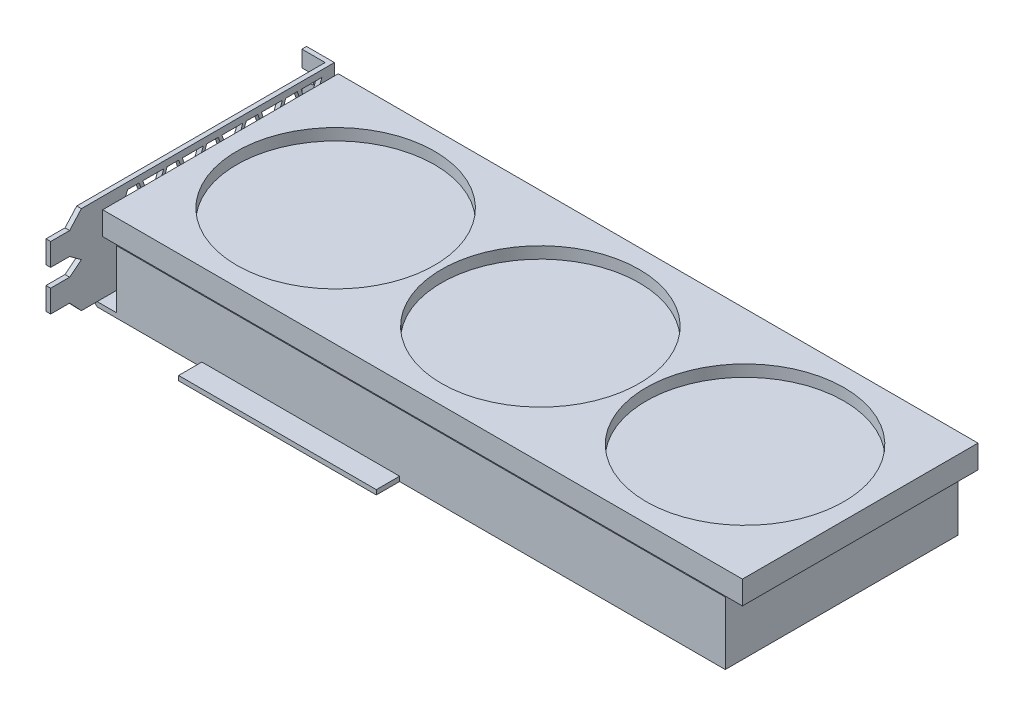
SolidWorks part; units mm, degrees
ref_plane "Front" through (0, 0, 0) normal (0, 0, 1) x (1, 0, 0)
ref_plane "Top" through (0, 0, 0) normal (0, 1, 0) x (1, 0, 0)
ref_plane "Right" through (0, 0, 0) normal (1, 0, 0) x (0, 0, -1)
sketch "Sketch5" plane through (0, 0, 0) normal (0, 1, 0) x (1, 0, 0)
  line L0 (-103.8802, -0.3761) -> (-58.8802, -0.3761)
  line L1 (-103.8802, 99.6239) -> (166.1198, 99.6239)
  line L2 (-103.8802, 99.6239) -> (-103.8802, -0.3761)
  line L4 (166.1198, 99.6239) -> (166.1198, -0.3761)
  line L6 (-58.8802, -0.3761) -> (-58.8802, -10.3761)
  line L7 (-58.8802, -10.3761) -> (26.1198, -10.3761)
  line L8 (26.1198, -0.3761) -> (26.1198, -10.3761)
  line L9 (26.1198, -0.3761) -> (166.1198, -0.3761)
  dimension "D1" = 100
  dimension "D2" = 270
  dimension "D3" = 10
  dimension "D4" = 85
  dimension "D5" = 45
extrude "Boss-Extrude3" add sketch "Sketch5" along normal blind 2 contours L2 L0 L6 L7 L8 L9 L4 L1
sketch "Sketch6" plane through (-103.8802, 0, 0) normal (-1, 0, 0) x (0, 0, 1)
  line L0 (20.3761, 24.7157) -> (20.3761, 34.3764)
  line L1 (-99.6239, 2) -> (20.3761, 2) construction
  line L2 (-99.6239, 2) -> (-99.6239, 40)
  line L3 (-99.6239, 40) -> (20.3761, 40) construction
  line L4 (20.3761, 2) -> (20.3761, 40) construction
  line L5 (20.3761, 34.3764) -> (12.2118, 34.3764)
  line L6 (12.2118, 34.3764) -> (7.1586, 40)
  line L7 (7.1586, 40) -> (-99.6239, 40)
  line L8 (20.3761, 24.7157) -> (12.2118, 24.7157)
  line L9 (12.2118, 24.7157) -> (7.1586, 21)
  line L10 (7.1586, 21) -> (12.2118, 17.008)
  line L11 (12.2118, 17.008) -> (20.3761, 17.008)
  line L12 (20.3761, 17.008) -> (20.3761, 7.3474)
  line L13 (20.3761, 7.3474) -> (12.2118, 7.3474)
  line L14 (12.2118, 7.3474) -> (7.1586, 2)
  line L15 (7.1586, 2) -> (-99.6239, 2)
  line L16 (-96.2244, 37.1678) -> (-87.2244, 37.1678)
  line L17 (-87.2244, 37.1678) -> (-89.2435, 31.6296)
  line L18 (-89.2435, 31.6296) -> (-94.2053, 31.6296)
  line L19 (-94.2053, 31.6296) -> (-96.2244, 37.1678)
  line L20 (-94.2053, 30.1428) -> (-89.2435, 30.1428)
  line L21 (-89.2435, 30.1428) -> (-87.2244, 24.6046)
  line L22 (-87.2244, 24.6046) -> (-96.2244, 24.6046)
  line L23 (-96.2244, 24.6046) -> (-94.2053, 30.1428)
  line L24 (-87.6768, 31.6186) -> (-85.6577, 37.1568)
  line L25 (-85.6577, 37.1568) -> (-80.6959, 37.1568)
  line L26 (-80.6959, 37.1568) -> (-78.6768, 31.6186)
  line L27 (-78.6768, 31.6186) -> (-87.6768, 31.6186)
  line L28 (-87.7069, 30.1428) -> (-78.7069, 30.1428)
  line L29 (-78.7069, 30.1428) -> (-80.726, 24.6046)
  line L30 (-80.726, 24.6046) -> (-85.6878, 24.6046)
  line L31 (-85.6878, 24.6046) -> (-87.7069, 30.1428)
  line L33 (-77.2053, 31.6296) -> (-79.2244, 37.1678)
  line L34 (-79.2244, 37.1678) -> (-70.2244, 37.1678)
  line L35 (-70.2244, 37.1678) -> (-72.2435, 31.6296)
  line L36 (-72.2435, 31.6296) -> (-77.2053, 31.6296)
  line L37 (-61.6768, 31.6186) -> (-70.6768, 31.6186)
  line L38 (-70.6768, 31.6186) -> (-68.6577, 37.1568)
  line L39 (-68.6577, 37.1568) -> (-63.6959, 37.1568)
  line L40 (-63.6959, 37.1568) -> (-61.6768, 31.6186)
  line L41 (-68.6878, 24.6046) -> (-70.7069, 30.1428)
  line L42 (-70.7069, 30.1428) -> (-61.7069, 30.1428)
  line L43 (-61.7069, 30.1428) -> (-63.726, 24.6046)
  line L44 (-63.726, 24.6046) -> (-68.6878, 24.6046)
  line L45 (-79.2244, 24.6046) -> (-77.2053, 30.1428)
  line L46 (-77.2053, 30.1428) -> (-72.2435, 30.1428)
  line L47 (-72.2435, 30.1428) -> (-70.2244, 24.6046)
  line L48 (-70.2244, 24.6046) -> (-79.2244, 24.6046)
  line L50 (-60.2053, 31.6296) -> (-62.2244, 37.1678)
  line L51 (-62.2244, 37.1678) -> (-53.2244, 37.1678)
  line L52 (-53.2244, 37.1678) -> (-55.2435, 31.6296)
  line L53 (-55.2435, 31.6296) -> (-60.2053, 31.6296)
  line L54 (-44.6768, 31.6186) -> (-53.6768, 31.6186)
  line L55 (-53.6768, 31.6186) -> (-51.6577, 37.1568)
  line L56 (-51.6577, 37.1568) -> (-46.6959, 37.1568)
  line L57 (-46.6959, 37.1568) -> (-44.6768, 31.6186)
  line L58 (-51.6878, 24.6046) -> (-53.7069, 30.1428)
  line L59 (-53.7069, 30.1428) -> (-44.7069, 30.1428)
  line L60 (-44.7069, 30.1428) -> (-46.726, 24.6046)
  line L61 (-46.726, 24.6046) -> (-51.6878, 24.6046)
  line L62 (-62.2244, 24.6046) -> (-60.2053, 30.1428)
  line L63 (-60.2053, 30.1428) -> (-55.2435, 30.1428)
  line L64 (-55.2435, 30.1428) -> (-53.2244, 24.6046)
  line L65 (-53.2244, 24.6046) -> (-62.2244, 24.6046)
  line L67 (-43.2053, 31.6296) -> (-45.2244, 37.1678)
  line L68 (-45.2244, 37.1678) -> (-36.2244, 37.1678)
  line L69 (-36.2244, 37.1678) -> (-38.2435, 31.6296)
  line L70 (-38.2435, 31.6296) -> (-43.2053, 31.6296)
  line L71 (-27.6768, 31.6186) -> (-36.6768, 31.6186)
  line L72 (-36.6768, 31.6186) -> (-34.6577, 37.1568)
  line L73 (-34.6577, 37.1568) -> (-29.6959, 37.1568)
  line L74 (-29.6959, 37.1568) -> (-27.6768, 31.6186)
  line L75 (-34.6878, 24.6046) -> (-36.7069, 30.1428)
  line L76 (-36.7069, 30.1428) -> (-27.7069, 30.1428)
  line L77 (-27.7069, 30.1428) -> (-29.726, 24.6046)
  line L78 (-29.726, 24.6046) -> (-34.6878, 24.6046)
  line L79 (-45.2244, 24.6046) -> (-43.2053, 30.1428)
  line L80 (-43.2053, 30.1428) -> (-38.2435, 30.1428)
  line L81 (-38.2435, 30.1428) -> (-36.2244, 24.6046)
  line L82 (-36.2244, 24.6046) -> (-45.2244, 24.6046)
  line L84 (-26.2053, 31.6296) -> (-28.2244, 37.1678)
  line L85 (-28.2244, 37.1678) -> (-19.2244, 37.1678)
  line L86 (-19.2244, 37.1678) -> (-21.2435, 31.6296)
  line L87 (-21.2435, 31.6296) -> (-26.2053, 31.6296)
  line L88 (-10.6768, 31.6186) -> (-19.6768, 31.6186)
  line L89 (-19.6768, 31.6186) -> (-17.6577, 37.1568)
  line L90 (-17.6577, 37.1568) -> (-12.6959, 37.1568)
  line L91 (-12.6959, 37.1568) -> (-10.6768, 31.6186)
  line L92 (-17.6878, 24.6046) -> (-19.7069, 30.1428)
  line L93 (-19.7069, 30.1428) -> (-10.7069, 30.1428)
  line L94 (-10.7069, 30.1428) -> (-12.726, 24.6046)
  line L95 (-12.726, 24.6046) -> (-17.6878, 24.6046)
  line L96 (-28.2244, 24.6046) -> (-26.2053, 30.1428)
  line L97 (-26.2053, 30.1428) -> (-21.2435, 30.1428)
  line L98 (-21.2435, 30.1428) -> (-19.2244, 24.6046)
  line L99 (-19.2244, 24.6046) -> (-28.2244, 24.6046)
  line L101 (-77.2053, 17.6296) -> (-79.2244, 23.1678)
  line L102 (-79.2244, 23.1678) -> (-70.2244, 23.1678)
  line L103 (-70.2244, 23.1678) -> (-72.2435, 17.6296)
  line L104 (-72.2435, 17.6296) -> (-77.2053, 17.6296)
  line L105 (-61.6768, 17.6186) -> (-70.6768, 17.6186)
  line L106 (-70.6768, 17.6186) -> (-68.6577, 23.1568)
  line L107 (-68.6577, 23.1568) -> (-63.6959, 23.1568)
  line L108 (-63.6959, 23.1568) -> (-61.6768, 17.6186)
  line L109 (-68.6878, 10.6046) -> (-70.7069, 16.1428)
  line L110 (-70.7069, 16.1428) -> (-61.7069, 16.1428)
  line L111 (-61.7069, 16.1428) -> (-63.726, 10.6046)
  line L112 (-63.726, 10.6046) -> (-68.6878, 10.6046)
  line L113 (-79.2244, 10.6046) -> (-77.2053, 16.1428)
  line L114 (-77.2053, 16.1428) -> (-72.2435, 16.1428)
  line L115 (-72.2435, 16.1428) -> (-70.2244, 10.6046)
  line L116 (-70.2244, 10.6046) -> (-79.2244, 10.6046)
  line L118 (-60.2053, 17.6296) -> (-62.2244, 23.1678)
  line L119 (-62.2244, 23.1678) -> (-53.2244, 23.1678)
  line L120 (-53.2244, 23.1678) -> (-55.2435, 17.6296)
  line L121 (-55.2435, 17.6296) -> (-60.2053, 17.6296)
  line L122 (-44.6768, 17.6186) -> (-53.6768, 17.6186)
  line L123 (-53.6768, 17.6186) -> (-51.6577, 23.1568)
  line L124 (-51.6577, 23.1568) -> (-46.6959, 23.1568)
  line L125 (-46.6959, 23.1568) -> (-44.6768, 17.6186)
  line L126 (-51.6878, 10.6046) -> (-53.7069, 16.1428)
  line L127 (-53.7069, 16.1428) -> (-44.7069, 16.1428)
  line L128 (-44.7069, 16.1428) -> (-46.726, 10.6046)
  line L129 (-46.726, 10.6046) -> (-51.6878, 10.6046)
  line L130 (-62.2244, 10.6046) -> (-60.2053, 16.1428)
  line L131 (-60.2053, 16.1428) -> (-55.2435, 16.1428)
  line L132 (-55.2435, 16.1428) -> (-53.2244, 10.6046)
  line L133 (-53.2244, 10.6046) -> (-62.2244, 10.6046)
  line L135 (-43.2053, 17.6296) -> (-45.2244, 23.1678)
  line L136 (-45.2244, 23.1678) -> (-36.2244, 23.1678)
  line L137 (-36.2244, 23.1678) -> (-38.2435, 17.6296)
  line L138 (-38.2435, 17.6296) -> (-43.2053, 17.6296)
  line L139 (-27.6768, 17.6186) -> (-36.6768, 17.6186)
  line L140 (-36.6768, 17.6186) -> (-34.6577, 23.1568)
  line L141 (-34.6577, 23.1568) -> (-29.6959, 23.1568)
  line L142 (-29.6959, 23.1568) -> (-27.6768, 17.6186)
  line L143 (-34.6878, 10.6046) -> (-36.7069, 16.1428)
  line L144 (-36.7069, 16.1428) -> (-27.7069, 16.1428)
  line L145 (-27.7069, 16.1428) -> (-29.726, 10.6046)
  line L146 (-29.726, 10.6046) -> (-34.6878, 10.6046)
  line L147 (-45.2244, 10.6046) -> (-43.2053, 16.1428)
  line L148 (-43.2053, 16.1428) -> (-38.2435, 16.1428)
  line L149 (-38.2435, 16.1428) -> (-36.2244, 10.6046)
  line L150 (-36.2244, 10.6046) -> (-45.2244, 10.6046)
  line L152 (-26.2053, 17.6296) -> (-28.2244, 23.1678)
  line L153 (-28.2244, 23.1678) -> (-19.2244, 23.1678)
  line L154 (-19.2244, 23.1678) -> (-21.2435, 17.6296)
  line L155 (-21.2435, 17.6296) -> (-26.2053, 17.6296)
  line L156 (-10.6768, 17.6186) -> (-19.6768, 17.6186)
  line L157 (-19.6768, 17.6186) -> (-17.6577, 23.1568)
  line L158 (-17.6577, 23.1568) -> (-12.6959, 23.1568)
  line L159 (-12.6959, 23.1568) -> (-10.6768, 17.6186)
  line L160 (-17.6878, 10.6046) -> (-19.7069, 16.1428)
  line L161 (-19.7069, 16.1428) -> (-10.7069, 16.1428)
  line L162 (-10.7069, 16.1428) -> (-12.726, 10.6046)
  line L163 (-12.726, 10.6046) -> (-17.6878, 10.6046)
  line L164 (-28.2244, 10.6046) -> (-26.2053, 16.1428)
  line L165 (-26.2053, 16.1428) -> (-21.2435, 16.1428)
  line L166 (-21.2435, 16.1428) -> (-19.2244, 10.6046)
  line L167 (-19.2244, 10.6046) -> (-28.2244, 10.6046)
  line L169 (-94.2053, 17.6296) -> (-96.2244, 23.1678)
  line L170 (-96.2244, 23.1678) -> (-87.2244, 23.1678)
  line L171 (-87.2244, 23.1678) -> (-89.2435, 17.6296)
  line L172 (-89.2435, 17.6296) -> (-94.2053, 17.6296)
  line L173 (-78.6768, 17.6186) -> (-87.6768, 17.6186)
  line L174 (-87.6768, 17.6186) -> (-85.6577, 23.1568)
  line L175 (-85.6577, 23.1568) -> (-80.6959, 23.1568)
  line L176 (-80.6959, 23.1568) -> (-78.6768, 17.6186)
  line L177 (-85.6878, 10.6046) -> (-87.7069, 16.1428)
  line L178 (-87.7069, 16.1428) -> (-78.7069, 16.1428)
  line L179 (-78.7069, 16.1428) -> (-80.726, 10.6046)
  line L180 (-80.726, 10.6046) -> (-85.6878, 10.6046)
  line L181 (-96.2244, 10.6046) -> (-94.2053, 16.1428)
  line L182 (-94.2053, 16.1428) -> (-89.2435, 16.1428)
  line L183 (-89.2435, 16.1428) -> (-87.2244, 10.6046)
  line L184 (-87.2244, 10.6046) -> (-96.2244, 10.6046)
  line L185 (41.1586, 26) -> (-65.6239, 26) [skipped]
  line L186 (7.1586, 26) -> (-99.6239, 26) [skipped]
  line L187 (58.1586, 26) -> (-48.6239, 26) [skipped]
  line L188 (75.1586, 26) -> (-31.6239, 26) [skipped]
  line L189 (24.1586, 26) -> (-82.6239, 26) [skipped]
  line L190 (41.1586, 40) -> (-65.6239, 40) [skipped]
  line L191 (58.1586, 40) -> (-48.6239, 40) [skipped]
  line L192 (75.1586, 40) -> (-31.6239, 40) [skipped]
  line L193 (24.1586, 40) -> (-82.6239, 40) [skipped]
  point P17 (20.3761, 21)
  dimension "D3" = 9
  dimension "D1" = 38
  dimension "D2" = 120
  dimension "D4" = 5
  dimension "D5" = 2
extrude "Boss-Extrude4" add sketch "Sketch6" along normal blind 2 separate body
sketch "Sketch7" plane through (0, 0, -99.6239) normal (0, 0, -1) x (-1, 0, 0)
  line L0 (115.8802, 6) -> (115.8802, 1)
  line L1 (103.8802, 40) -> (115.8802, 40)
  line L2 (103.8802, 40) -> (103.8802, 6)
  line L3 (103.8802, 6) -> (115.8802, 6) construction
  line L5 (115.8802, 1) -> (110.8802, 1)
  line L6 (110.8802, 1) -> (110.8802, 6)
  line L7 (110.8802, 6) -> (103.8802, 6)
  line L8 (115.8802, 40) -> (115.8802, 33)
  line L9 (115.8802, 33) -> (110.8802, 33)
  line L10 (110.8802, 33) -> (110.8802, 29)
  line L11 (110.8802, 29) -> (115.8802, 29)
  line L13 (115.8802, 11) -> (110.8802, 11)
  line L14 (110.8802, 11) -> (110.8802, 15)
  line L15 (110.8802, 15) -> (115.8802, 15)
  line L17 (115.8802, 29) -> (115.8802, 15)
  line L18 (115.8802, 11) -> (115.8802, 6)
  line L19 (108.8802, 25.0527) -> (108.8802, 20.9473) construction
  line L20 (110.2816, 25.0527) -> (110.2816, 20.9473)
  line L21 (107.4787, 25.0527) -> (107.4787, 20.9473)
  arc A0 (110.2816, 25.0527) -> (107.4787, 25.0527) centre (108.8802, 25.0527) ccw
  arc A1 (107.4787, 20.9473) -> (110.2816, 20.9473) centre (108.8802, 20.9473) ccw
  point P15 (108.8802, 23)
  dimension "D1" = 34
  dimension "D2" = 12
  dimension "D3" = 5
  dimension "D4" = 5
  dimension "D5" = 7
  dimension "D6" = 5
  dimension "D7" = 29
  dimension "D8" = 4
  dimension "D9" = 5
  dimension "D10" = 17
extrude "Boss-Extrude5" add sketch "Sketch7" along normal blind 2
sketch "Sketch8" plane through (0, 2, 0) normal (0, 1, 0) x (1, 0, 0)
  line L0 (-103.8802, 99.6239) -> (166.1198, 99.6239) construction
  line L1 (-95.5937, 99.6239) -> (166.1198, 99.6239)
  line L2 (-95.5937, 99.6239) -> (-95.5937, -0.3761)
  line L3 (-95.5937, -0.3761) -> (166.1198, -0.3761)
  line L4 (166.1198, 99.6239) -> (166.1198, -0.3761)
extrude "Boss-Extrude6" add sketch "Sketch8" along normal blind 25
sketch "Sketch10" plane through (0, 27, 0) normal (0, 1, 0) x (1, 0, 0)
  line L0 (-103.8802, 99.6239) -> (-103.8802, -7.1586) construction
  line L1 (-101.8802, 101.2748) -> (173.1198, 101.2748)
  line L2 (-101.8802, 101.2748) -> (-101.8802, 0)
  line L3 (-101.8802, 0) -> (173.1198, 0)
  line L4 (173.1198, 101.2748) -> (173.1198, 0)
  dimension "D1" = 2
  dimension "D2" = 275
extrude "Boss-Extrude12" add sketch "Sketch10" along normal blind 10
sketch "Sketch11" plane through (0, 37, 0) normal (0, 1, 0) x (1, 0, 0)
  line L1 (173.1198, 101.2748) -> (-101.8802, 101.2748) construction
  line L2 (173.1198, 0) -> (173.1198, 101.2748) construction
  circle A0 centre (-52.3802, 50.6374) radius 42.5
  circle A1 centre (35.6198, 50.6374) radius 42.5
  circle A2 centre (123.6198, 50.6374) radius 42.5
  point P8 (-54.1574, 51.8056)
  point P9 (35.6198, 101.2748)
  point P12 (173.1198, 50.6374)
  dimension "D1" = 85
  dimension "D2" = 3
extrude "Cut-Extrude1" cut sketch "Sketch11" against normal blind 5
sketch "Sketch12" plane through (0, 0, -99.6239) normal (0, 0, -1) x (-1, 0, 0)
  line L0 (103.8802, 2) -> (105.8802, 2)
  line L1 (105.8802, 2) -> (103.8802, 0)
  line L2 (103.8802, 0) -> (103.8802, 2)
extrude "Boss-Extrude13" add sketch "Sketch12" against normal up to surface (100 mm away) up to face at (-13.2229, 6.2, 0.3761)
